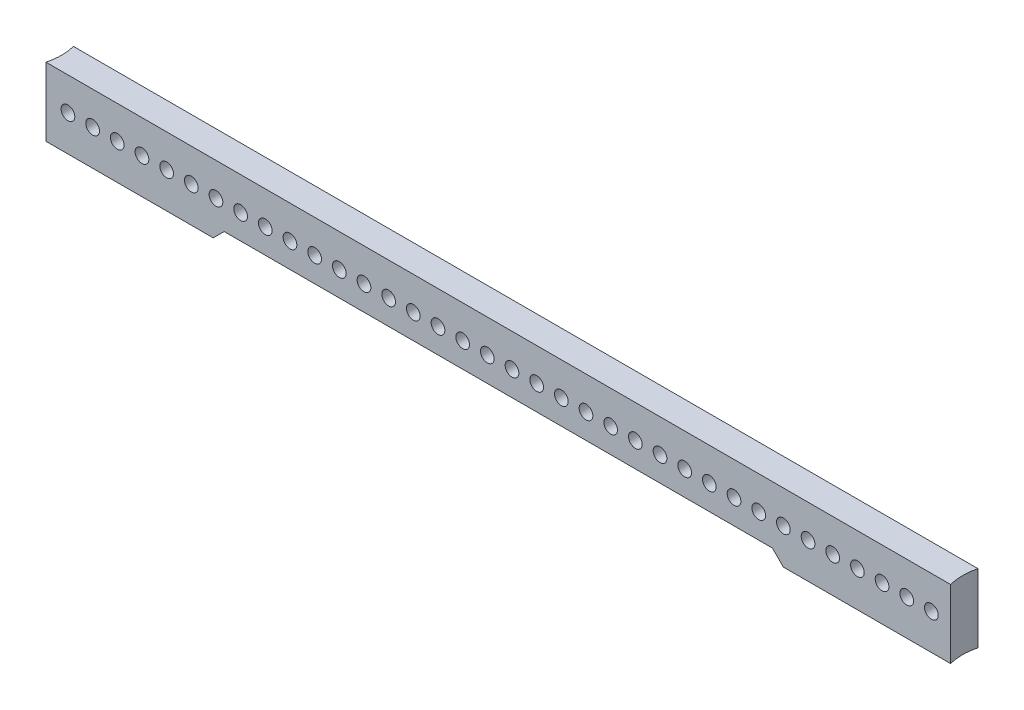
SolidWorks part; units mm, degrees
ref_plane "Front Plane" through (0, 0, 0) normal (0, 0, 1) x (1, 0, 0)
ref_plane "Top Plane" through (0, 0, 0) normal (0, 1, 0) x (1, 0, 0)
ref_plane "Right Plane" through (0, 0, 0) normal (1, 0, 0) x (0, 0, -1)
sketch "Sketch1" plane through (0, 0, 0) normal (0, 0, 1) x (1, 0, 0)
  line L0 (-215.9, 0) -> (215.9, 0)
  line L2 (215.9, -31.75) -> (132.08, -31.75)
  line L3 (132.08, -31.75) -> (127, -26.67)
  line L4 (127, -26.67) -> (-127, -26.67)
  line L5 (-127, -26.67) -> (-132.08, -31.75)
  line L6 (-132.08, -31.75) -> (-215.9, -31.75)
  line L8 (-215.9, -31.75) -> (-215.9, 0)
  line L9 (215.9, 0) -> (215.9, -31.75)
  dimension "D1" = 431.8
  dimension "D2" = 31.75
  dimension "D3" = 254
  dimension "D4" = 5.08
extrude "Boss-Extrude1" add sketch "Sketch1" along normal blind 12.7
sketch "Sketch2" plane through (0, 0, 0) normal (0, 1, 0) x (1, 0, 0)
  line L4 (-209.55, 0) -> (-215.9, 0)
  line L5 (-215.9, 0) -> (-215.9, -12.7)
  line L6 (-215.9, -12.7) -> (-209.55, -12.7)
  line L7 (215.9, -12.7) -> (-215.9, -12.7) construction
  arc A0 (-209.55, 0) -> (-209.55, -12.7) centre (-234.1434, -6.35) cw
  dimension "D1" = 25.4
  dimension "D2" = 6.35
extrude "Cut-Extrude1" cut sketch "Sketch2" against normal up to next
mirror "Mirror1" about plane through (0, 0, 0) normal (1, 0, 0) of "Cut-Extrude1"
sketch "Sketch3" plane through (0, 0, 12.7) normal (0, 0, 1) x (1, 0, 0)
  line L0 (209.55, 0) -> (-209.55, 0) construction
  line L1 (-209.55, -31.75) -> (-209.55, 0) construction
  line L2 (-199.39, -15.24) -> (-187.96, -15.24) construction
  circle A0 centre (-199.39, -15.24) radius 3.175
  circle A1 centre (-187.96, -15.24) radius 3.175
  circle A2 centre (-176.53, -15.24) radius 3.175
  circle A3 centre (-165.1, -15.24) radius 3.175
  circle A4 centre (-153.67, -15.24) radius 3.175
  circle A5 centre (-142.24, -15.24) radius 3.175
  circle A6 centre (-130.81, -15.24) radius 3.175
  circle A7 centre (-119.38, -15.24) radius 3.175
  circle A8 centre (-107.95, -15.24) radius 3.175
  circle A9 centre (-96.52, -15.24) radius 3.175
  circle A10 centre (-85.09, -15.24) radius 3.175
  circle A11 centre (-73.66, -15.24) radius 3.175
  circle A12 centre (-62.23, -15.24) radius 3.175
  circle A13 centre (-50.8, -15.24) radius 3.175
  circle A14 centre (-39.37, -15.24) radius 3.175
  circle A15 centre (-27.94, -15.24) radius 3.175
  circle A16 centre (-16.51, -15.24) radius 3.175
  circle A17 centre (-5.08, -15.24) radius 3.175
  circle A18 centre (6.35, -15.24) radius 3.175
  circle A19 centre (17.78, -15.24) radius 3.175
  circle A20 centre (29.21, -15.24) radius 3.175
  circle A21 centre (40.64, -15.24) radius 3.175
  circle A22 centre (52.07, -15.24) radius 3.175
  circle A23 centre (63.5, -15.24) radius 3.175
  circle A24 centre (74.93, -15.24) radius 3.175
  circle A25 centre (86.36, -15.24) radius 3.175
  circle A26 centre (97.79, -15.24) radius 3.175
  circle A27 centre (109.22, -15.24) radius 3.175
  circle A28 centre (120.65, -15.24) radius 3.175
  circle A29 centre (132.08, -15.24) radius 3.175
  circle A30 centre (143.51, -15.24) radius 3.175
  circle A31 centre (154.94, -15.24) radius 3.175
  circle A32 centre (166.37, -15.24) radius 3.175
  circle A33 centre (177.8, -15.24) radius 3.175
  circle A34 centre (189.23, -15.24) radius 3.175
  circle A35 centre (200.66, -15.24) radius 3.175
  dimension "D1" = 6.35
  dimension "D2" = 15.24
  dimension "D3" = 10.16
  dimension "D5" = 11.43
  dimension "D4" = 36
extrude "Cut-Extrude2" cut sketch "Sketch3" against normal through all
